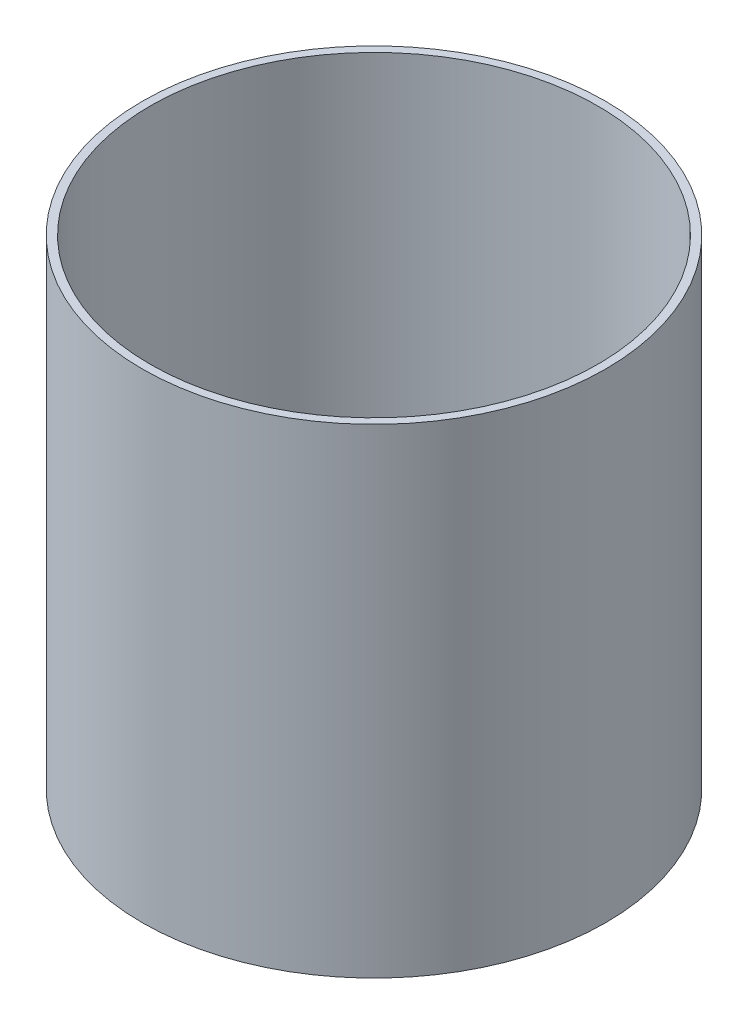
SolidWorks part; units mm, degrees
ref_plane "Front Plane" through (0, 0, 0) normal (0, 0, 1) x (1, 0, 0)
ref_plane "Top Plane" through (0, 0, 0) normal (0, 1, 0) x (1, 0, 0)
ref_plane "Right Plane" through (0, 0, 0) normal (1, 0, 0) x (0, 0, -1)
sketch "Sketch1" plane through (0, 0, 0) normal (0, 1, 0) x (1, 0, 0)
  circle A0 centre (0, 0) radius 145
  circle A1 centre (0, 0) radius 140
  dimension "D1" = 290
  dimension "D2" = 280
extrude "Boss-Extrude1" add sketch "Sketch1" along normal blind 300
